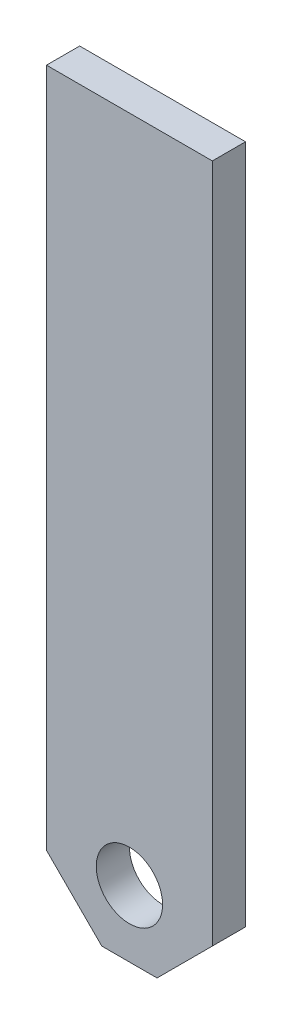
SolidWorks part; units mm, degrees
ref_plane "Спереди" through (0, 0, 0) normal (0, 0, 1) x (1, 0, 0)
ref_plane "Сверху" through (0, 0, 0) normal (0, 1, 0) x (1, 0, 0)
ref_plane "Справа" through (0, 0, 0) normal (1, 0, 0) x (0, 0, -1)
sketch "Эскиз1" plane through (0, 0, 0) normal (0, 0, 1) x (1, 0, 0)
  line L1 (-15, 0) -> (15, 0)
  line L2 (-15, 0) -> (-15, -133)
  line L3 (-15, -133) -> (15, -133)
  line L4 (15, 0) -> (15, -133)
  dimension "D1" = 133
extrude "Бобышка-Вытянуть1" add sketch "Эскиз1" against normal blind 6 contours L3 L4 L1 L2
chamfer "Фаска1" distance 10 angle 45 2 edges at (-15, -133, -3) (15, -133, -3)
sketch "Эскиз2" plane through (0, 0, 0) normal (0, 0, 1) x (1, 0, 0)
  line L0 (0, -133) -> (0, -121) construction
  line L1 (-5, -133) -> (5, -133) construction
  circle A0 centre (0, -121) radius 6
  dimension "D2" = 12
  dimension "D1" = 12
extrude "Вырез-Вытянуть1" cut sketch "Эскиз2" against normal through all
